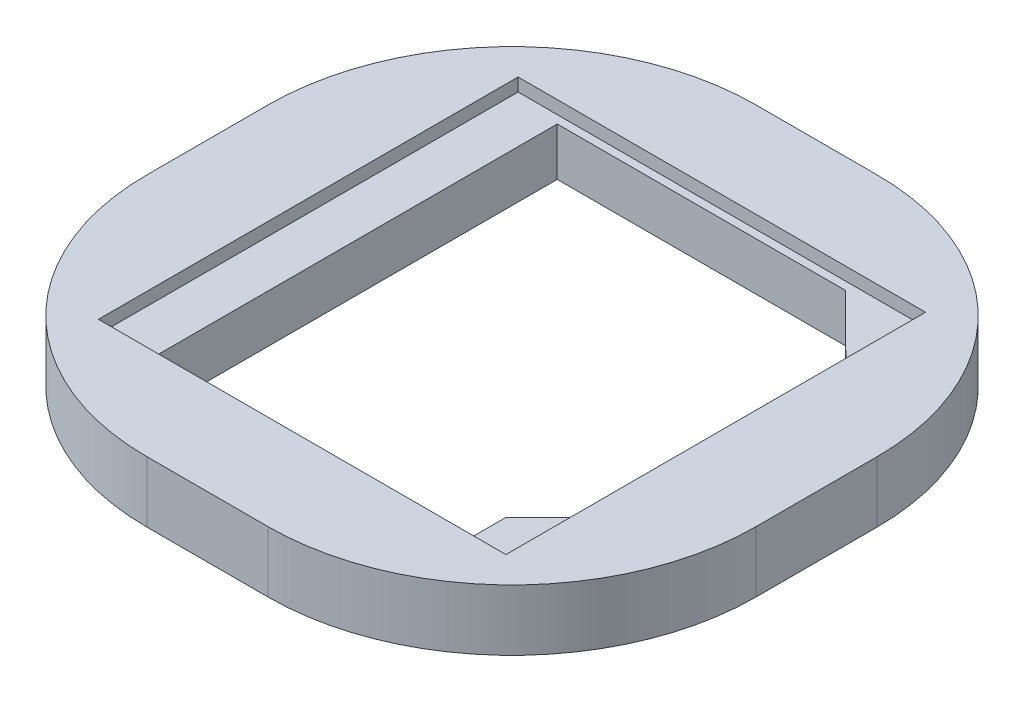
SolidWorks part; units mm, degrees
ref_plane "Front Plane" through (0, 0, 0) normal (0, 0, 1) x (1, 0, 0)
ref_plane "Top Plane" through (0, 0, 0) normal (0, 1, 0) x (1, 0, 0)
ref_plane "Right Plane" through (0, 0, 0) normal (1, 0, 0) x (0, 0, -1)
sketch "Sketch2" plane through (0, 0, 0) normal (0, 1, 0) x (1, 0, 0)
  line L1 (-37.45, -37.45) -> (37.45, -37.45)
  line L2 (-37.45, -37.45) -> (-37.45, 37.45)
  line L3 (-37.45, 37.45) -> (37.45, 37.45)
  line L4 (37.45, -37.45) -> (37.45, 37.45)
  line L5 (-37.45, -37.45) -> (37.45, 37.45) construction
  line L6 (-37.45, 37.45) -> (37.45, -37.45) construction
  point P0 (0, 0)
  dimension "D1" = 74.9
  dimension "D2" = 74.9
extrude "Base" add sketch "Sketch2" along normal blind 7.5
sketch "Sketch3" plane through (0, 7.5, 0) normal (0, 1, 0) x (1, 0, 0)
  line L1 (-25.05, -25.8) -> (25.05, -25.8)
  line L2 (-25.05, -25.8) -> (-25.05, 25.8)
  line L3 (-25.05, 25.8) -> (25.05, 25.8)
  line L4 (25.05, -25.8) -> (25.05, 25.8)
  line L5 (-25.05, -25.8) -> (25.05, 25.8) construction
  line L6 (-25.05, 25.8) -> (25.05, -25.8) construction
  point P0 (0, 0)
  dimension "D1" = 50.1
  dimension "D2" = 51.6
extrude "Slot" cut sketch "Sketch3" against normal blind 1.6
sketch "Sketch4" plane through (0, 5.9, 0) normal (0, 1, 0) x (1, 0, 0)
  line L0 (-19.238, -25.8) -> (-19.238, 24.8007)
  line L1 (-19.238, 24.8007) -> (16.1992, 24.8007)
  line L3 (16.1992, 24.8007) -> (25.05, 16)
  line L5 (25.05, 16) -> (25.05, -14.6954)
  line L6 (25.05, -25.8) -> (25.05, 25.8) construction
  line L7 (25.05, -14.6954) -> (19.4909, -20.2861)
  line L8 (19.4909, -20.2861) -> (19.4909, -25.8)
  line L9 (-25.05, -25.8) -> (25.05, -25.8) construction
  line L10 (19.4909, -25.8) -> (-19.238, -25.8)
  line L11 (25.05, -25.8) -> (25.05, 25.8) construction
extrude "Cut-Extrude2" cut sketch "Sketch4" against normal up to surface (5.9 mm away) up to face at (0, 0, 0)
fillet "Fillet1" radius 30 4 edges at (37.45, 3.75, -37.45) (37.45, 3.75, 37.45) (-37.45, 3.75, 37.45) (-37.45, 3.75, -37.45)
